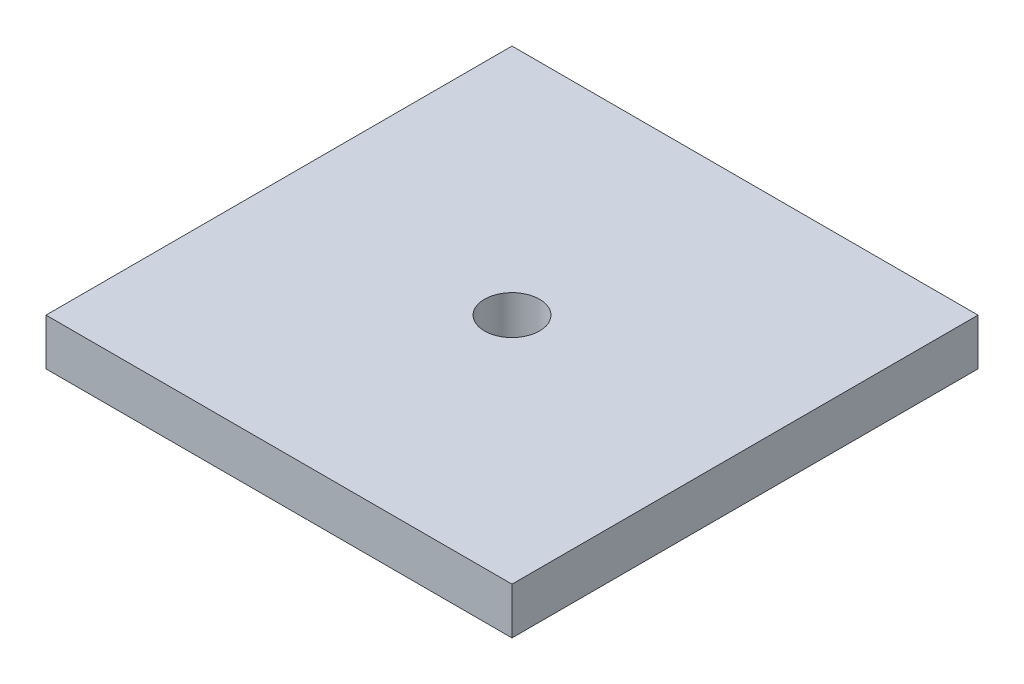
SolidWorks part; units mm, degrees
material "Pine"
ref_plane "Front Plane" through (0, 0, 0) normal (0, 0, 1) x (1, 0, 0)
ref_plane "Top Plane" through (0, 0, 0) normal (0, 1, 0) x (1, 0, 0)
ref_plane "Right Plane" through (0, 0, 0) normal (1, 0, 0) x (0, 0, -1)
sketch "Sketch1" plane through (0, 0, 0) normal (0, 1, 0) x (1, 0, 0)
  line L1 (63.5, -63.5) -> (-63.5, -63.5)
  line L2 (63.5, -63.5) -> (63.5, 63.5)
  line L3 (63.5, 63.5) -> (-63.5, 63.5)
  line L4 (-63.5, -63.5) -> (-63.5, 63.5)
  line L5 (63.5, -63.5) -> (-63.5, 63.5) construction
  line L6 (63.5, 63.5) -> (-63.5, -63.5) construction
  circle A0 centre (0, 0) radius 7.5057
  point P0 (0, 0)
  dimension "D3" = 15.0114
  dimension "D1" = 127
  dimension "D2" = 127
extrude "Boss-Extrude1" add sketch "Sketch1" along normal blind 12.7
equation "\"D2@Sketch1\"=\"D1@Sketch1\""
